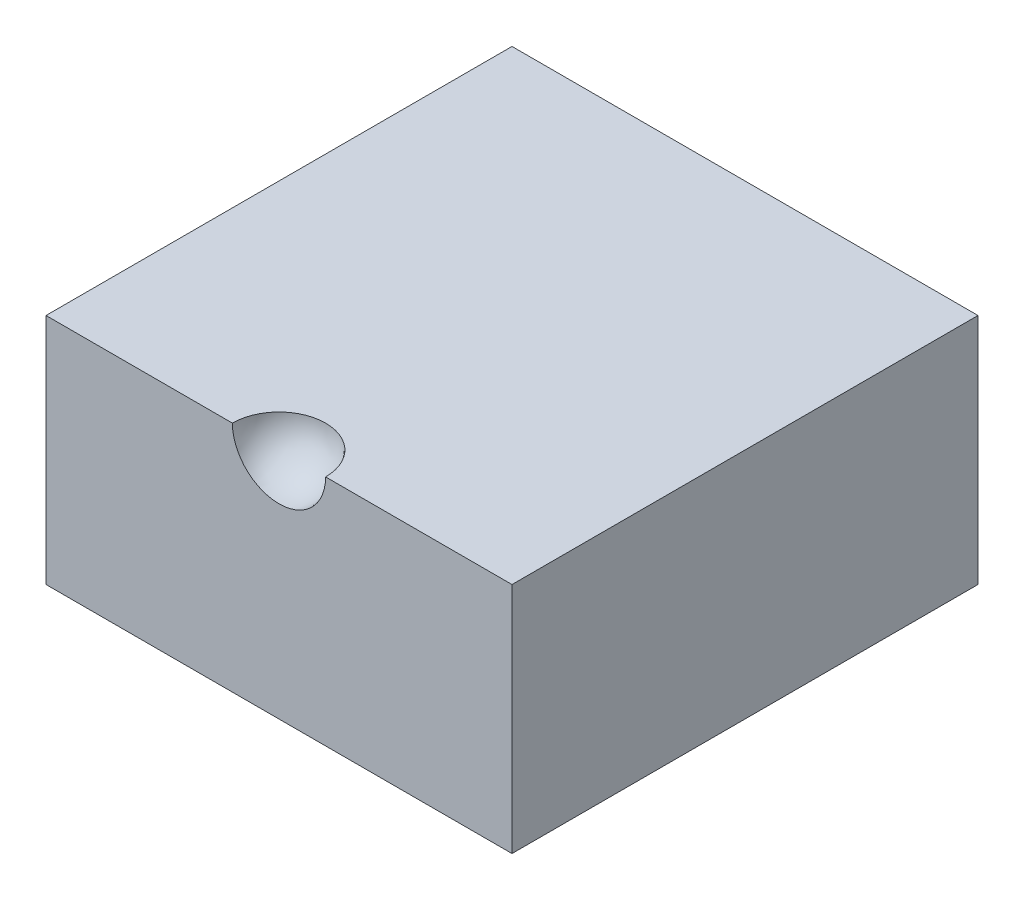
SolidWorks part; units mm, degrees
ref_plane "Front Plane" through (0, 0, 0) normal (0, 0, 1) x (1, 0, 0)
ref_plane "Top Plane" through (0, 0, 0) normal (0, 1, 0) x (1, 0, 0)
ref_plane "Right Plane" through (0, 0, 0) normal (1, 0, 0) x (0, 0, -1)
sketch "Sketch2" plane through (0, 0, 0) normal (0, 1, 0) x (1, 0, 0)
  line L1 (-25, 25) -> (25, 25)
  line L2 (-25, 25) -> (-25, -25)
  line L3 (-25, -25) -> (25, -25)
  line L4 (25, 25) -> (25, -25)
  line L5 (-25, 25) -> (25, -25) construction
  line L6 (-25, -25) -> (25, 25) construction
  point P0 (0, 0)
  dimension "D1" = 50
  dimension "D2" = 50
extrude "Boss-Extrude1" add sketch "Sketch2" against normal blind 25
sketch "Sketch3" plane through (0, 0, 0) normal (0, 1, 0) x (1, 0, 0)
  line L0 (0, 0) -> (0, -25) construction
  line L1 (-25, -25) -> (25, -25) construction
  line L2 (-5, -25) -> (5, -25)
  arc A0 (-5, -25) -> (5, -25) centre (0, -25) cw
  dimension "D1" = 5
revolve "Cut-Revolve1" cut sketch "Sketch3" angle 360 about L2
